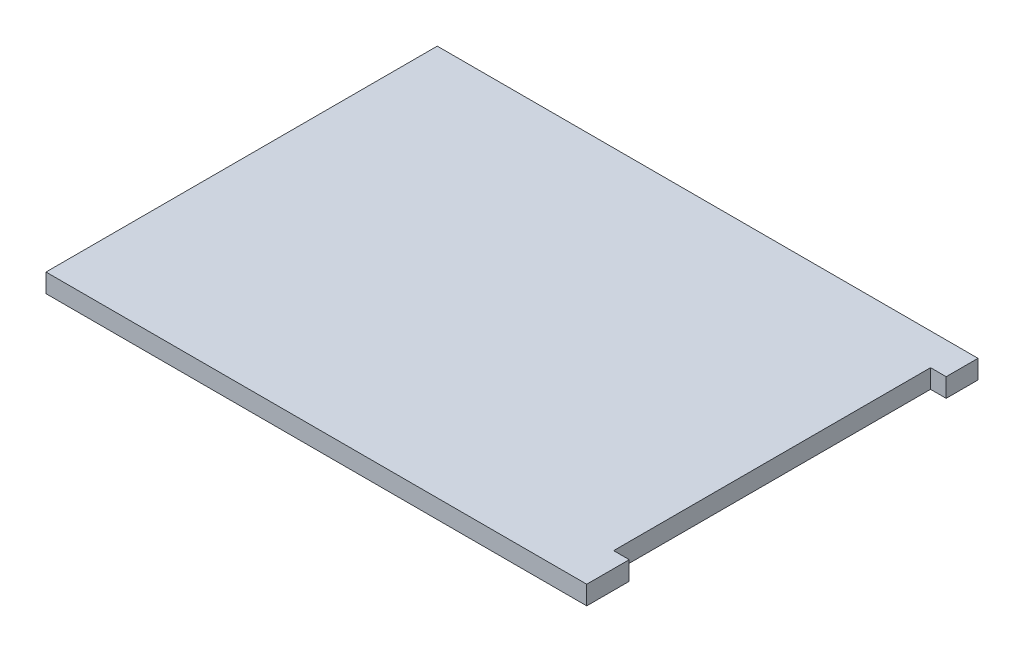
SolidWorks part; units mm, degrees
ref_plane "前视基准面" through (0, 0, 0) normal (0, 0, 1) x (1, 0, 0)
ref_plane "上视基准面" through (0, 0, 0) normal (0, 1, 0) x (1, 0, 0)
ref_plane "右视基准面" through (0, 0, 0) normal (1, 0, 0) x (0, 0, -1)
other "Configuration Table"
sketch "草图1" plane through (0, 0, 0) normal (0, 1, 0) x (1, 0, 0)
  line L0 (-28.7, 0) -> (28.7, 0) construction
  line L1 (-28.7, -21.6) -> (28.7, -21.6) construction
  line L2 (-28.7, -21.6) -> (-28.7, 21.6) construction
  line L3 (-28.7, 21.6) -> (28.7, 21.6) construction
  line L4 (28.7, -21.6) -> (28.7, 21.6) construction
  line L5 (-28.7, -21.6) -> (28.7, 21.6) construction
  line L6 (-28.7, 21.6) -> (28.7, -21.6) construction
  line L8 (-31.4, -25) -> (37.7, -25)
  line L9 (-31.4, -25) -> (-31.4, 25)
  line L10 (-31.4, 25) -> (37.7, 25)
  line L11 (37.7, -25) -> (37.7, 25)
  line L12 (-31.4, -25) -> (37.7, 25) construction
  line L13 (-31.4, 25) -> (37.7, -25) construction
  point P0 (0, 0)
  point P8 (3.15, 0)
  dimension "D1" = 57.4
  dimension "D2" = 43.2
  dimension "D3" = 50
  dimension "D4" = 69.1
  dimension "D5" = 9
extrude "凸台-拉伸1" add sketch "草图1" along normal blind 2.4
sketch "草图2" plane through (0, 0, 0) normal (0, -1, 0) x (1, 0, 0)
  line L0 (37.7, 25) -> (37.7, -25) construction
  line L1 (35.7033, -20.9323) -> (39.6967, -20.9323)
  line L2 (35.7033, -20.9323) -> (35.7033, 19.5677)
  line L3 (35.7033, 19.5677) -> (39.6967, 19.5677)
  line L4 (39.6967, -20.9323) -> (39.6967, 19.5677)
  line L5 (35.7033, -20.9323) -> (39.6967, 19.5677) construction
  line L6 (35.7033, 19.5677) -> (39.6967, -20.9323) construction
  point P0 (37.7, -0.6823)
  dimension "D1" = 40.5
extrude "切除-拉伸1" cut sketch "草图2" against normal blind 2.4
sketch "草图3" [suppressed] plane through (0, 2.4, 0) normal (0, 1, 0) x (1, 0, 0)
  line L0 (0, 0.6823) -> (35.7033, 0.6823) construction
  line L1 (35.7033, -19.5677) -> (35.7033, 20.9323) construction
  line L3 (-19.8116, -14.2282) -> (19.8116, -14.2282)
  line L4 (-19.8116, -14.2282) -> (-19.8116, 15.5928)
  line L5 (-19.8116, 15.5928) -> (19.8116, 15.5928)
  line L6 (19.8116, -14.2282) -> (19.8116, 15.5928)
  line L7 (-19.8116, -14.2282) -> (19.8116, 15.5928) construction
  line L8 (-19.8116, 15.5928) -> (19.8116, -14.2282) construction
  point P11 (35.7033, 0.6823)
  dimension "D1" = 29.821
  dimension "D2" = 39.6232
scale "缩放比例1" [suppressed]
